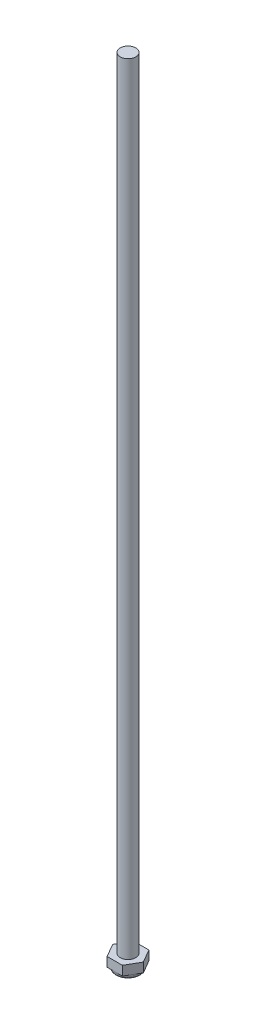
SolidWorks part; units mm, degrees
ref_plane "Alzado" through (0, 0, 0) normal (0, 0, 1) x (1, 0, 0)
ref_plane "Planta" through (0, 0, 0) normal (0, 1, 0) x (1, 0, 0)
ref_plane "Vista lateral" through (0, 0, 0) normal (1, 0, 0) x (0, 0, -1)
sketch "Croquis1" plane through (0, 0, 0) normal (0, 1, 0) x (1, 0, 0)
  line L1 (4.9075, -8.5) -> (9.815, 0)
  line L2 (9.815, 0) -> (4.9075, 8.5)
  line L3 (4.9075, 8.5) -> (-4.9075, 8.5)
  line L4 (-4.9075, 8.5) -> (-9.815, 0)
  line L5 (-9.815, 0) -> (-4.9075, -8.5)
  line L6 (-4.9075, -8.5) -> (4.9075, -8.5)
  circle A0 centre (0, 0) radius 8.5 construction
  dimension "D1" = 17
extrude "Saliente-Extruir1" add sketch "Croquis1" along normal blind 6
sketch "Croquis2" plane through (0, 0, 0) normal (0, -1, 0) x (1, 0, 0)
  circle A0 centre (0, 0) radius 8.1
  dimension "D1" = 16.2
extrude "Saliente-Extruir2" add sketch "Croquis2" along normal blind 3
fillet "Redondeo1" radius 2 1 edges at (0, -3, -8.1)
sketch "Croquis3" plane through (0, 6, 0) normal (0, 1, 0) x (1, 0, 0)
  circle A0 centre (0, 0) radius 5
  dimension "D1" = 10
extrude "Saliente-Extruir3" add sketch "Croquis3" along normal blind 500
